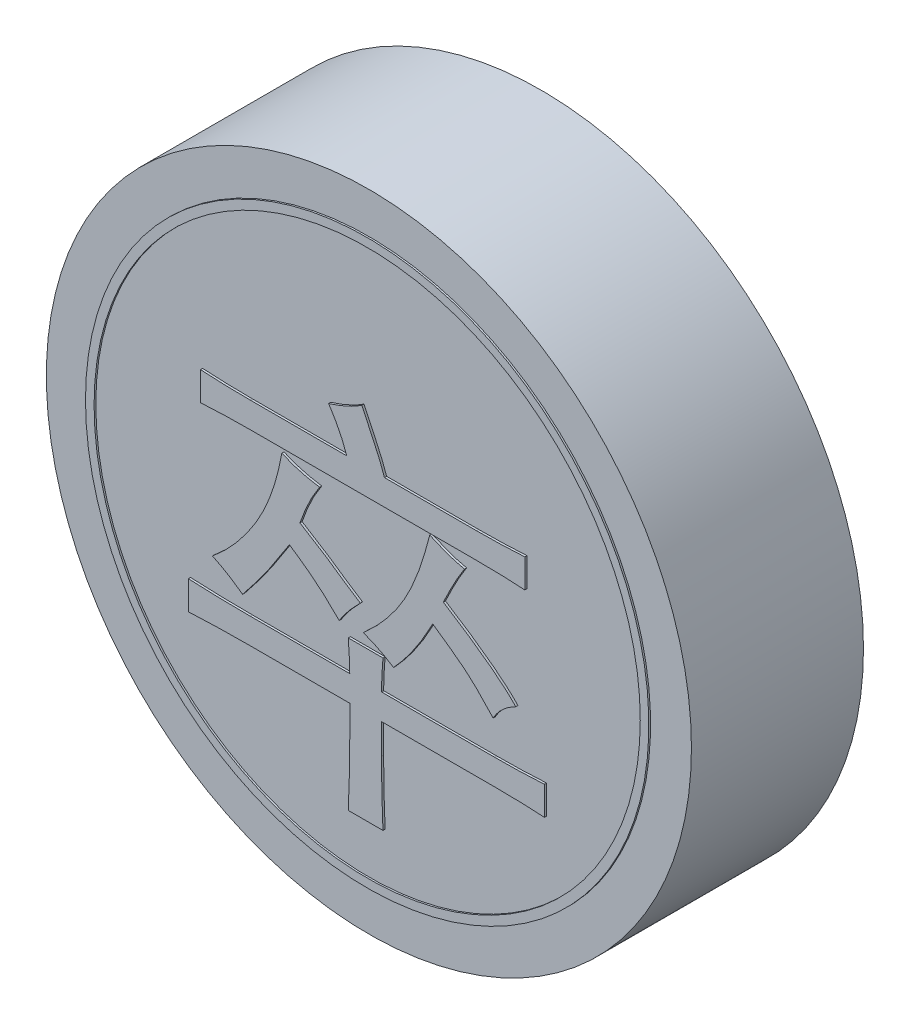
SolidWorks part; units mm, degrees
ref_plane "前视基准面" through (0, 0, 0) normal (0, 0, 1) x (1, 0, 0)
ref_plane "上视基准面" through (0, 0, 0) normal (0, 1, 0) x (1, 0, 0)
ref_plane "右视基准面" through (0, 0, 0) normal (1, 0, 0) x (0, 0, -1)
other "Configuration Table"
sketch "草图1" plane through (0, 0, 0) normal (0, 0, 1) x (1, 0, 0)
  circle A0 centre (0, 0) radius 15
  dimension "D1" = 30
extrude "Diameter30_Height8" add sketch "草图1" against normal blind 8
sketch "草图2" plane through (0, 0, 0) normal (0, 0, 1) x (1, 0, 0)
  text T0 "卒" font "SimHei" height 12
extrude "Character_卒" add sketch "草图2" along normal blind 0.1
sketch "草图3" plane through (0, 0, 0) normal (0, 0, 1) x (1, 0, 0)
  circle A0 centre (0, 0) radius 13.1
  circle A1 centre (0, 0) radius 12.7
extrude "Ink_ring" add sketch "草图3" along normal blind 0.08
